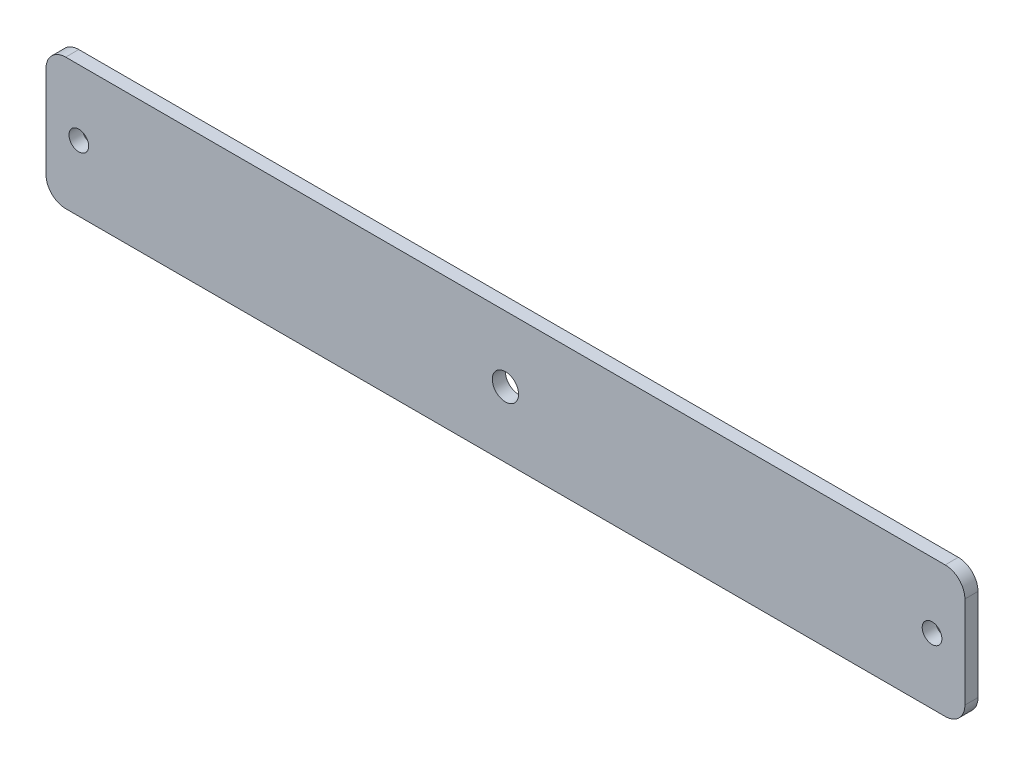
SolidWorks part; units mm, degrees
ref_plane "Ön Düzlem" through (0, 0, 0) normal (0, 0, 1) x (1, 0, 0)
ref_plane "Üst Düzlem" through (0, 0, 0) normal (0, 1, 0) x (1, 0, 0)
ref_plane "Sağ Düzlem" through (0, 0, 0) normal (1, 0, 0) x (0, 0, -1)
sketch "Çizim1" plane through (0, 0, 0) normal (0, 0, 1) x (1, 0, 0)
  line L0 (0, 0) -> (-66.0536, 0)
  line L1 (-66.0536, 0) -> (-66.0536, 20)
  line L2 (-66.0536, 20) -> (73.9464, 20)
  line L3 (73.9464, 20) -> (73.9464, 0)
  line L4 (73.9464, 0) -> (0, 0)
  circle A0 centre (3.9464, 10) radius 2
  circle A1 centre (-61.0536, 10) radius 1.5
  circle A2 centre (68.9464, 10) radius 1.5
  dimension "D4" = 4
  dimension "D6" = 3
  dimension "D7" = 3
  dimension "D1" = 140
  dimension "D2" = 20
  dimension "D3" = 70
  dimension "D5" = 10
  dimension "D8" = 10
  dimension "D9" = 10
  dimension "D10" = 5
  dimension "D11" = 5
extrude "Yükseklik-Ekstrüzyon1" add sketch "Çizim1" along normal blind 2
fillet "Radyus1" radius 3 4 edges at (73.9464, 20, 1) (73.9464, 0, 1) (-66.0536, 0, 1) (-66.0536, 20, 1)
